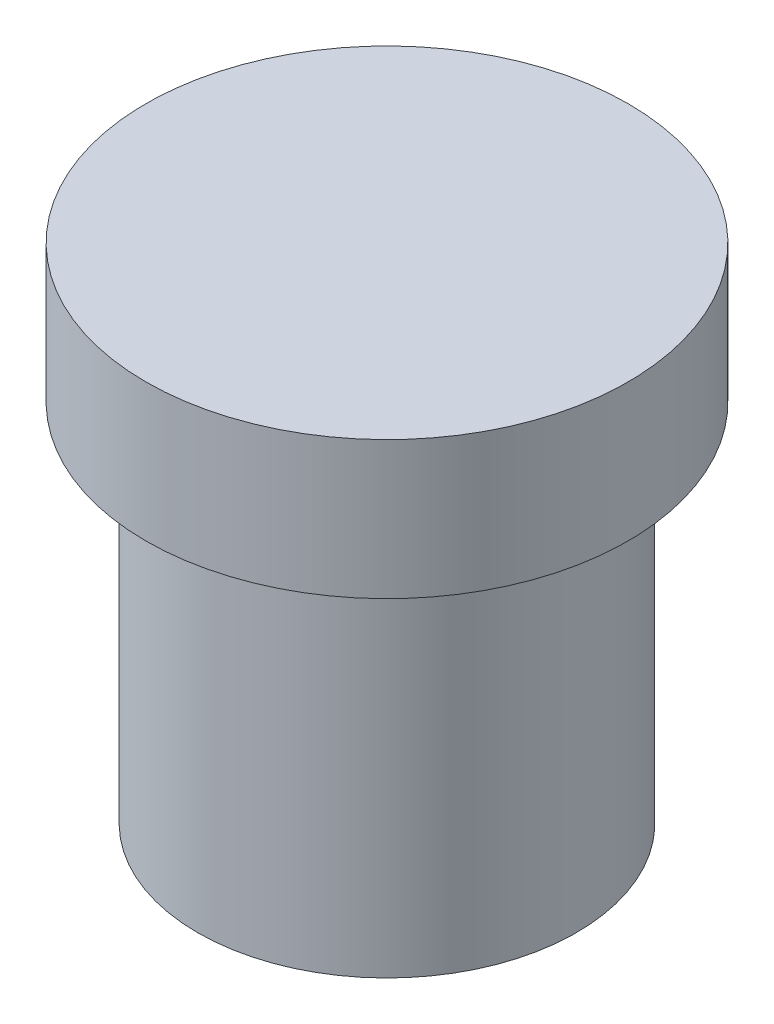
SolidWorks part; units mm, degrees
ref_plane "Front Plane" through (0, 0, 0) normal (0, 0, 1) x (1, 0, 0)
ref_plane "Top Plane" through (0, 0, 0) normal (0, 1, 0) x (1, 0, 0)
ref_plane "Right Plane" through (0, 0, 0) normal (1, 0, 0) x (0, 0, -1)
sketch "Sketch1" plane through (0, 0, 0) normal (0, 1, 0) x (1, 0, 0)
  circle A0 centre (0, 0) radius 1.25
  dimension "D1" = 2.5
extrude "Boss-Extrude1" add sketch "Sketch1" along normal blind 2.5 contours A0
sketch "Sketch2" plane through (0, 2.5, 0) normal (0, 1, 0) x (1, 0, 0)
  circle A0 centre (0, 0) radius 6.875
  dimension "D1" = 13.75
extrude "Boss-Extrude2" add sketch "Sketch2" along normal blind 13.25
sketch "Sketch3" plane through (0, 15.75, 0) normal (0, 1, 0) x (1, 0, 0)
  circle A0 centre (0, 0) radius 8.75
  dimension "D1" = 17.5
extrude "Boss-Extrude3" add sketch "Sketch3" along normal blind 5
